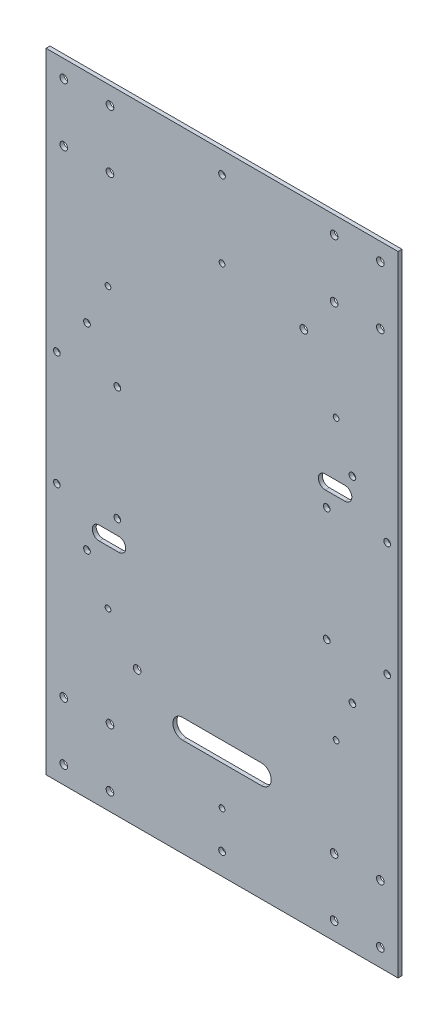
SolidWorks part; units mm, degrees
ref_plane "Alzado" through (0, 0, 0) normal (0, 0, 1) x (1, 0, 0)
ref_plane "Planta" through (0, 0, 0) normal (0, 1, 0) x (1, 0, 0)
ref_plane "Vista lateral" through (0, 0, 0) normal (1, 0, 0) x (0, 0, -1)
sketch "Croquis1" plane through (0, 0, 0) normal (0, 0, 1) x (1, 0, 0)
  line L1 (-89.5, -160) -> (89.5, -160)
  line L2 (-89.5, -160) -> (-89.5, 160)
  line L3 (-89.5, 160) -> (89.5, 160)
  line L4 (89.5, -160) -> (89.5, 160)
  line L5 (-89.5, -160) -> (89.5, 160) construction
  line L6 (-89.5, 160) -> (89.5, -160) construction
  point P0 (0, 0)
  dimension "D1" = 179
  dimension "D2" = 320
extrude "Saliente-Extruir1" add sketch "Croquis1" along normal blind 2
sketch "lineas guia" plane through (0, 0, 2) normal (0, 0, 1) x (1, 0, 0)
  line L0 (-89.5, 160) -> (89.5, -160) construction
  line L1 (89.5, 0) -> (-89.5, 0) construction
  line L2 (-89.5, -160) -> (89.5, 160) construction
  line L3 (-89.5, 160) -> (-89.5, -160) construction
  point P14 (0, 0)
sketch "superior bores" plane through (0, 0, 2) normal (0, 0, 1) x (1, 0, 0)
  point P0 (66.31, 49.42)
  point P1 (0, 149)
  point P5 (-68.69, 49.42)
  point P6 (-68.69, -50.58)
  point P7 (0, -149)
  point P8 (66.31, -50.58)
  dimension "D2" = 149
  dimension "D3" = 149
  dimension "D5" = 49.42
  dimension "D6" = 66.31
  dimension "D4" = 2
  dimension "D1" = 2
sketch "mid bores" plane through (0, 0, 2) normal (0, 0, 1) x (1, 0, 0)
  point P0 (-58, 71)
  point P1 (0, 110)
  point P2 (0, -130)
  point P4 (58, 71)
  point P6 (58, -71)
  point P8 (-58, -71)
  dimension "D1" = 110
  dimension "D2" = 58
  dimension "D3" = 71
  dimension "D4" = 130
  dimension "D5" = 2
  dimension "D6" = 2
sketch "regul bores" plane through (0, 0, 2) normal (0, 0, 1) x (1, 0, 0)
  point P0 (-84, 29)
  point P1 (-53.2526, 29)
  point P3 (-53.2526, -29)
  point P5 (-84, -29)
  point P7 (53.2526, 29)
  point P9 (84, 29)
  point P11 (84, -29)
  point P13 (53.2526, -29)
sketch "wheel bores" plane through (0, 0, 2) normal (0, 0, 1) x (1, 0, 0)
  line L0 (-89.5, 160) -> (-89.5, -160) construction
  line L1 (-89.5, -160) -> (89.5, -160) construction
  point P0 (-80.5, -121.42)
  point P1 (-57, -121.42)
  point P2 (-57, -151)
  point P3 (-80.5, -151)
  dimension "D1" = 23.5
  dimension "D2" = 29.58
  dimension "D3" = 9
  dimension "D4" = 9
sketch "power supply bores" plane through (0, 0, 0) normal (0, 0, -1) x (-1, 0, 0)
  point P0 (-41.6, 101.785)
  point P1 (43.2, -90.415)
hole_wizard "Taladro de margen para M31" positions "Croquis3" profile "Croquis4" hole size "M3" standard "Ansi Metric" end condition through all
sketch "Croquis3" plane through (0, 0, 2) normal (0, 0, 1) x (1, 0, 0)
  point P0 (0, 149)
  point P3 (-68.69, 49.42)
  point P6 (-68.69, -50.58)
  point P9 (0, -149)
  point P12 (66.31, -50.58)
  point P15 (66.31, 49.42)
sketch "Croquis4" plane through (0, 149, 2) normal (1, 0, 0) x (0, -1, 0)
  line L0 (0, 0) -> (0, 2)
  line L1 (0, 2) -> (1.7, 2)
  line L2 (1.7, 2) -> (1.7, 0)
  line L5 (1.7, 0) -> (0, 0)
  line L11 (0, -6.35) -> (0, 107.95) construction
  dimension "Diámetro de taladro hasta el siguiente" = 3.4
  dimension "Profundidad de taladro hasta el siguiente" = 2
hole_wizard "Taladro de margen para M2.51" positions "Croquis5" profile "Croquis6" hole size "M2.5" standard "Ansi Metric" end condition through all
sketch "Croquis5" plane through (0, 0, 2) normal (0, 0, 1) x (1, 0, 0)
  point P0 (0, 110)
  point P3 (-58, 71)
  point P6 (-58, -71)
  point P9 (0, -130)
  point P12 (58, -71)
  point P15 (58, 71)
sketch "Croquis6" plane through (0, 110, 2) normal (1, 0, 0) x (0, -1, 0)
  line L0 (0, 0) -> (0, 2)
  line L1 (0, 2) -> (1.45, 2)
  line L2 (1.45, 2) -> (1.45, 0)
  line L5 (1.45, 0) -> (0, 0)
  line L11 (0, -6.35) -> (0, 107.95) construction
  dimension "Diámetro de taladro hasta el siguiente" = 2.9
  dimension "Profundidad de taladro hasta el siguiente" = 2
hole_wizard "Taladro de margen para M32" positions "Croquis8" profile "Croquis9" hole size "M3" standard "Ansi Metric" end condition through all
sketch "Croquis8" plane through (0, 0, 2) normal (0, 0, 1) x (1, 0, 0)
  point P0 (-84, 29)
  point P3 (-84, -29)
  point P6 (-53.2526, 29)
  point P9 (-53.2526, -29)
  point P12 (53.2526, 29)
  point P15 (84, 29)
  point P18 (84, -29)
  point P21 (53.2526, -29)
sketch "Croquis9" plane through (-84, 29, 2) normal (1, 0, 0) x (0, -1, 0)
  line L0 (0, 0) -> (0, 2)
  line L1 (0, 2) -> (1.7, 2)
  line L2 (1.7, 2) -> (1.7, 0)
  line L5 (1.7, 0) -> (0, 0)
  line L11 (0, -6.35) -> (0, 107.95) construction
  dimension "Diámetro de taladro hasta el siguiente" = 3.4
  dimension "Profundidad de taladro hasta el siguiente" = 2
sketch "Croquis10" plane through (0, 0, 2) normal (0, 0, 1) x (1, 0, 0)
  line L0 (-62.5, -40) -> (-52.5, -40) construction
  line L1 (-62.5, -36.5) -> (-52.5, -36.5)
  line L2 (-62.5, -43.5) -> (-52.5, -43.5)
  line L3 (52.5, 40) -> (62.5, 40) construction
  line L4 (52.5, 43.5) -> (62.5, 43.5)
  line L5 (52.5, 36.5) -> (62.5, 36.5)
  arc A0 (-62.5, -36.5) -> (-62.5, -43.5) centre (-62.5, -40) ccw
  arc A1 (-52.5, -43.5) -> (-52.5, -36.5) centre (-52.5, -40) ccw
  arc A2 (52.5, 43.5) -> (52.5, 36.5) centre (52.5, 40) ccw
  arc A3 (62.5, 36.5) -> (62.5, 43.5) centre (62.5, 40) ccw
  point P2 (-57.5, -40)
  point P8 (57.5, 40)
  dimension "D1" = 7
  dimension "D2" = 10
  dimension "D3" = 57.5
  dimension "D4" = 40
  dimension "D5" = 7
  dimension "D6" = 10
  dimension "D7" = 40
  dimension "D8" = 57.5
extrude "Cortar-Extruir1" cut sketch "Croquis10" against normal through all
hole_wizard "Taladro de margen para M3.51" positions "Croquis12" profile "Croquis13" hole size "M3.5" standard "Ansi Metric" end condition through all
sketch "Croquis12" plane through (0, 0, 2) normal (0, 0, 1) x (1, 0, 0)
  point P0 (-80.5, -121.42)
  point P3 (-57, -121.42)
  point P6 (-57, -151)
  point P9 (-80.5, -151)
sketch "Croquis13" plane through (-80.5, -121.42, 2) normal (1, 0, 0) x (0, -1, 0)
  line L0 (0, 0) -> (0, 2)
  line L1 (0, 2) -> (1.95, 2)
  line L2 (1.95, 2) -> (1.95, 0)
  line L5 (1.95, 0) -> (0, 0)
  line L11 (0, -6.35) -> (0, 107.95) construction
  dimension "Diámetro de taladro hasta el siguiente" = 3.9
  dimension "Profundidad de taladro hasta el siguiente" = 2
mirror "Simetría3" about plane through (0, 0, 0) normal (0, 1, 0) of "Taladro de margen para M3.51"
mirror "Simetría4" about plane through (0, 0, 0) normal (1, 0, 0) of "Simetría3", "Taladro de margen para M3.51"
hole_wizard "Taladro de margen para M3.52" positions "Croquis15" profile "Croquis16" hole size "M3.5" standard "Ansi Metric" end condition through all
sketch "Croquis15" plane through (0, 0, 0) normal (0, 0, -1) x (-1, 0, 0)
  point P0 (-41.6, 101.785)
  point P3 (43.2, -90.415)
sketch "Croquis16" plane through (41.6, 101.785, 0) normal (1, 0, 0) x (0, 1, 0)
  line L0 (0, 0) -> (0, 2)
  line L1 (0, 2) -> (1.95, 2)
  line L2 (1.95, 2) -> (1.95, 0)
  line L5 (1.95, 0) -> (0, 0)
  line L11 (0, -6.35) -> (0, 107.95) construction
  dimension "Diámetro de taladro hasta el siguiente" = 3.9
  dimension "Profundidad de taladro hasta el siguiente" = 2
sketch "Croquis17" plane through (0, 0, 0) normal (0, 0, -1) x (-1, 0, 0)
  line L0 (20, -105) -> (-20, -105) construction
  line L1 (20, -110) -> (-20, -110)
  line L2 (20, -100) -> (-20, -100)
  arc A0 (20, -110) -> (20, -100) centre (20, -105) ccw
  arc A1 (-20, -100) -> (-20, -110) centre (-20, -105) ccw
  point P2 (0, -105)
  dimension "D1" = 40
  dimension "D2" = 10
  dimension "D3" = 105
extrude "Cortar-Extruir2" cut sketch "Croquis17" against normal through all
